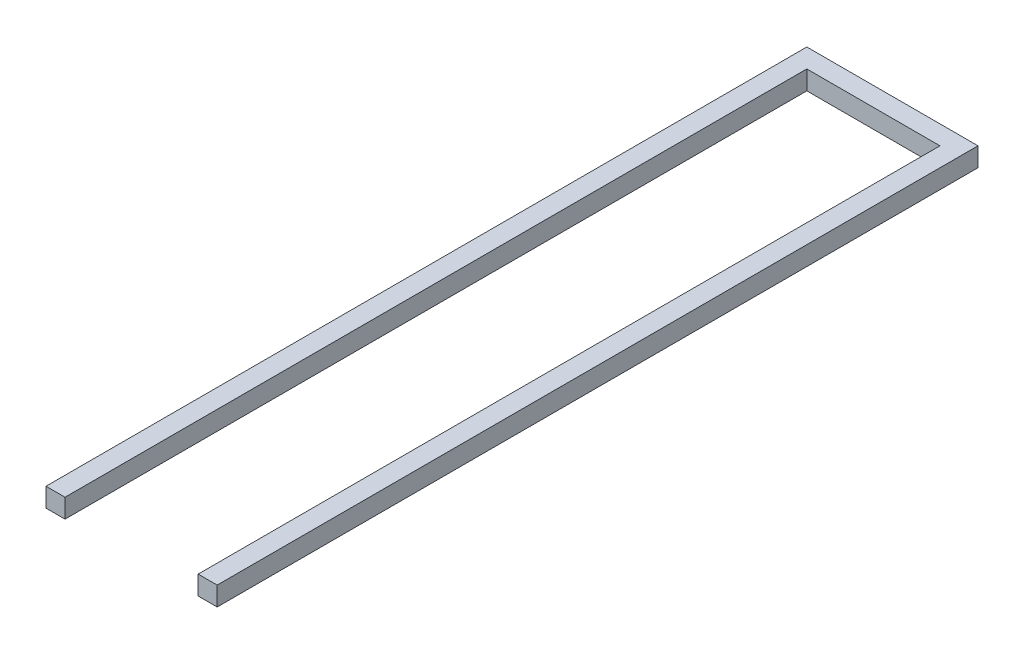
SolidWorks part; units mm, degrees
ref_plane "前视基准面" through (0, 0, 0) normal (0, 0, 1) x (1, 0, 0)
ref_plane "上视基准面" through (0, 0, 0) normal (0, 1, 0) x (1, 0, 0)
ref_plane "右视基准面" through (0, 0, 0) normal (1, 0, 0) x (0, 0, -1)
other "Configuration Table"
sketch "草图1" plane through (0, 0, 0) normal (0, 0, 1) x (1, 0, 0)
  line L1 (-225, -25) -> (-175, -25)
  line L2 (-225, -25) -> (-225, 25)
  line L3 (-225, 25) -> (-175, 25)
  line L4 (-175, -25) -> (-175, 25)
  line L5 (-225, -25) -> (-175, 25) construction
  line L6 (-225, 25) -> (-175, -25) construction
  point P0 (-200, 0)
extrude "凸台-拉伸1" add sketch "草图1" along normal blind 2000
sketch "草图2" plane through (0, 0, 0) normal (0, 0, 1) x (1, 0, 0)
  line L1 (175, -25) -> (225, -25)
  line L2 (175, -25) -> (175, 25)
  line L3 (175, 25) -> (225, 25)
  line L4 (225, -25) -> (225, 25)
  line L5 (175, -25) -> (225, 25) construction
  line L6 (175, 25) -> (225, -25) construction
  point P0 (200, 0)
extrude "凸台-拉伸2" add sketch "草图2" along normal blind 2000
sketch "草图3" plane through (0, 0, 0) normal (0, 0, 1) x (1, 0, 0)
  line L0 (225, 25) -> (175, 25) construction
  line L1 (-200, -25) -> (200, -25)
  line L2 (-200, -25) -> (-200, 25)
  line L3 (-200, 25) -> (200, 25)
  line L4 (200, -25) -> (200, 25)
  line L5 (-200, -25) -> (200, 25) construction
  line L6 (-200, 25) -> (200, -25) construction
  point P0 (0, 0)
extrude "凸台-拉伸3" add sketch "草图3" along normal blind 50
sketch "草图4" plane through (0, 0, 0) normal (0, 0, 1) x (1, 0, 0)
  line L0 (225, 25) -> (-225, 25) construction
  line L1 (-200, -25) -> (200, -25)
  line L2 (-200, -25) -> (-200, 25)
  line L3 (-200, 25) -> (200, 25)
  line L4 (200, -25) -> (200, 25)
  line L5 (-200, -25) -> (200, 25) construction
  line L6 (-200, 25) -> (200, -25) construction
  point P0 (0, 0)
extrude "凸台-拉伸4" add sketch "草图4" along normal blind 50
sketch "草图5" plane through (0, 0, 0) normal (0, 0, 1) x (1, 0, 0)
  line L0 (225, 25) -> (-225, 25) construction
  line L1 (-200, -25) -> (200, -25)
  line L2 (-200, -25) -> (-200, 25)
  line L3 (-200, 25) -> (200, 25)
  line L4 (200, -25) -> (200, 25)
  line L5 (-200, -25) -> (200, 25) construction
  line L6 (-200, 25) -> (200, -25) construction
  point P0 (0, 0)
extrude "凸台-拉伸5" add sketch "草图5" along normal blind 50
sketch "草图6" plane through (0, 0, 0) normal (0, 0, 1) x (1, 0, 0)
  line L0 (225, 25) -> (-225, 25) construction
  line L1 (-200, -25) -> (200, -25)
  line L2 (-200, -25) -> (-200, 25)
  line L3 (-200, 25) -> (200, 25)
  line L4 (200, -25) -> (200, 25)
  line L5 (-200, -25) -> (200, 25) construction
  line L6 (-200, 25) -> (200, -25) construction
  point P0 (0, 0)
extrude "凸台-拉伸6" add sketch "草图6" along normal blind 50
sketch "草图7" plane through (0, 0, 0) normal (0, 0, 1) x (1, 0, 0)
  line L0 (225, 25) -> (-225, 25) construction
  line L1 (-200, -25) -> (200, -25)
  line L2 (-200, -25) -> (-200, 25)
  line L3 (-200, 25) -> (200, 25)
  line L4 (200, -25) -> (200, 25)
  line L5 (-200, -25) -> (200, 25) construction
  line L6 (-200, 25) -> (200, -25) construction
  point P0 (0, 0)
extrude "凸台-拉伸7" add sketch "草图7" along normal blind 50
